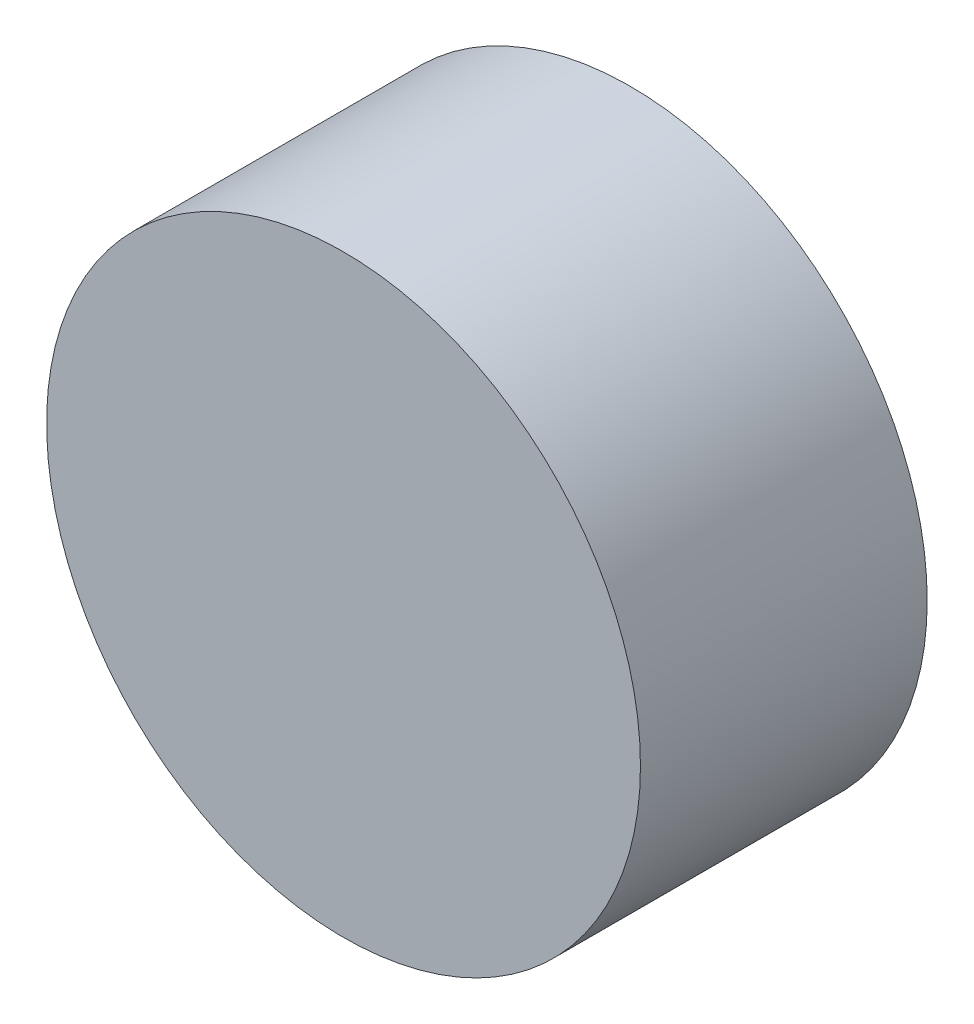
SolidWorks part; units mm, degrees
ref_plane "前视基准面" through (0, 0, 0) normal (0, 0, 1) x (1, 0, 0)
ref_plane "上视基准面" through (0, 0, 0) normal (0, 1, 0) x (1, 0, 0)
ref_plane "右视基准面" through (0, 0, 0) normal (1, 0, 0) x (0, 0, -1)
other "Configuration Table"
sketch "草图1" plane through (0, 0, 0) normal (0, 0, 1) x (1, 0, 0)
  circle A0 centre (0, 0) radius 35
extrude "外形" add sketch "草图1" along normal blind 33.8 from offset 0
